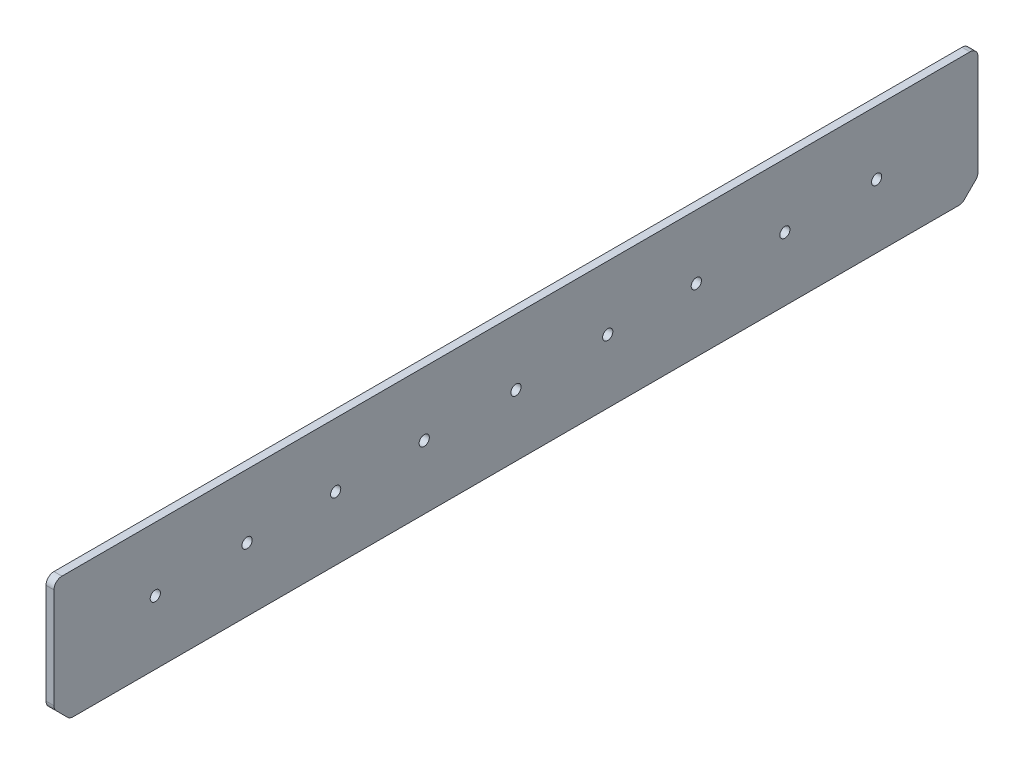
SolidWorks part; units mm, degrees
ref_plane "Front Plane" through (0, 0, 0) normal (0, 0, 1) x (1, 0, 0)
ref_plane "Top Plane" through (0, 0, 0) normal (0, 1, 0) x (1, 0, 0)
ref_plane "Right Plane" through (0, 0, 0) normal (1, 0, 0) x (0, 0, -1)
sketch "Sketch1" plane through (0, 0, 0) normal (1, 0, 0) x (0, 0, -1)
  line L1 (0, 0) -> (368.3, 0)
  line L2 (0, 0) -> (0, 50.8)
  line L3 (0, 50.8) -> (368.3, 50.8)
  line L4 (368.3, 0) -> (368.3, 50.8)
  dimension "D1" = 50.8
  dimension "D2" = 368.3
extrude "Boss-Extrude1" add sketch "Sketch1" along normal blind 3.175
sketch "Sketch2" plane through (3.175, 0, 0) normal (1, 0, 0) x (0, 0, -1)
  circle A0 centre (327.9054, 25.4) radius 2.032 construction
  circle A1 centre (291.3294, 25.4) radius 2.032 construction
  circle A2 centre (256.0234, 25.4) radius 2.032 construction
  circle A3 centre (220.7174, 25.4) radius 2.032 construction
  circle A4 centre (184.15, 24.6062) radius 2.032 construction
  circle A5 centre (147.5826, 25.4) radius 2.032 construction
  circle A6 centre (112.2766, 25.4) radius 2.032 construction
  circle A7 centre (76.9706, 25.4) radius 2.032 construction
  circle A8 centre (40.3946, 25.4) radius 2.032 construction
  circle A9 centre (327.9054, 25.4) radius 2.032
  circle A10 centre (291.3294, 25.4) radius 2.032
  circle A11 centre (256.0234, 25.4) radius 2.032
  circle A12 centre (220.7174, 25.4) radius 2.032
  circle A13 centre (184.15, 24.6062) radius 2.032
  circle A14 centre (147.5826, 25.4) radius 2.032
  circle A15 centre (112.2766, 25.4) radius 2.032
  circle A16 centre (76.9706, 25.4) radius 2.032
  circle A17 centre (40.3946, 25.4) radius 2.032
extrude "Cut-Extrude1" cut sketch "Sketch2" against normal through all
chamfer "Chamfer1" distance 6.35 angle 45 2 edges at (1.5875, 0, 0) (1.5875, 0, -368.3)
fillet "Fillet1" radius 3.175 6 edges at (1.5875, 0, -361.95) (1.5875, 6.35, -368.3) (1.5875, 50.8, -368.3) (1.5875, 0, -6.35) (1.5875, 6.35, 0) (1.5875, 50.8, 0)
